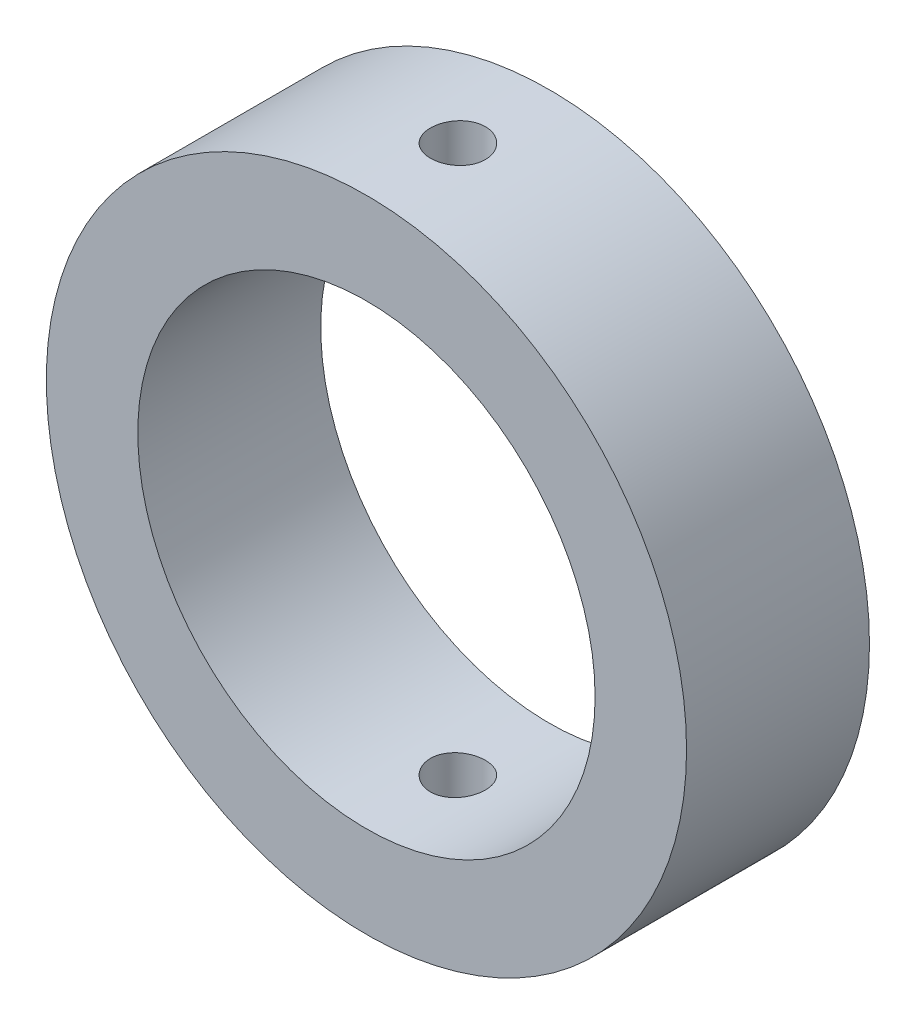
SolidWorks part; units mm, degrees
ref_plane "Front Plane" through (0, 0, 0) normal (0, 0, 1) x (1, 0, 0)
ref_plane "Top Plane" through (0, 0, 0) normal (0, 1, 0) x (1, 0, 0)
ref_plane "Right Plane" through (0, 0, 0) normal (1, 0, 0) x (0, 0, -1)
sketch "Sketch2" plane through (0, 0, 0) normal (0, 0, 1) x (1, 0, 0)
  circle A0 centre (0, 0) radius 35
  circle A1 centre (0, 0) radius 25
  dimension "D1" = 70
  dimension "D2" = 50
extrude "Boss-Extrude1" add sketch "Sketch2" along normal blind 20
sketch "Sketch3" plane through (0, 0, 0) normal (0, 1, 0) x (1, 0, 0)
  circle A0 centre (0, -10) radius 3
  point P2 (0, 0)
  dimension "D1" = 6
  dimension "D2" = 10
extrude "Cut-Extrude1" cut sketch "Sketch3" against normal through all both and the other way through all
